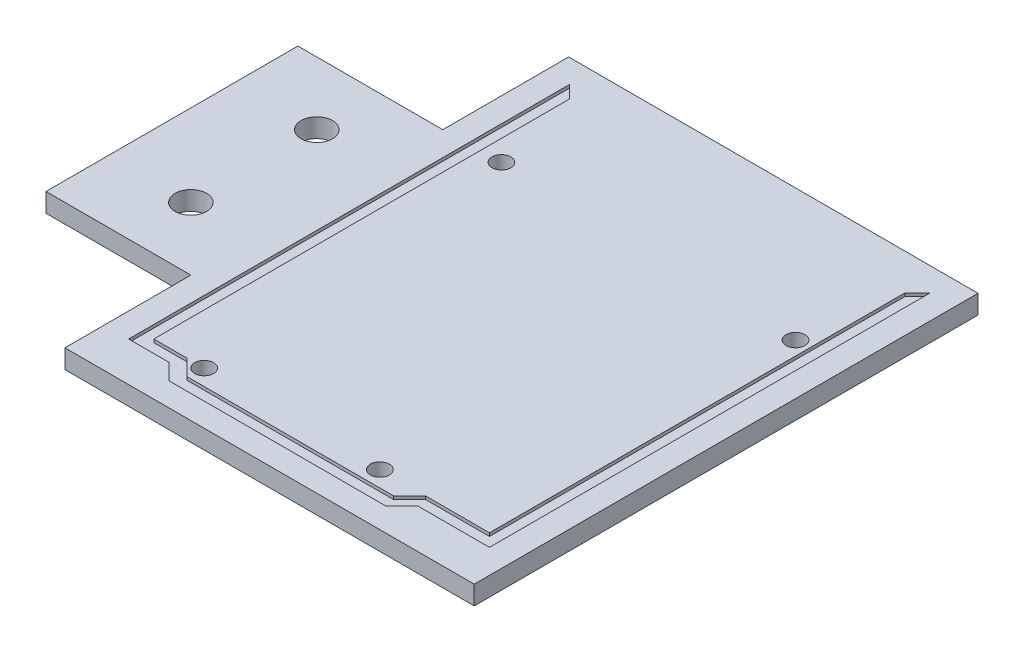
SolidWorks part; units mm, degrees
ref_plane "Front Plane" through (0, 0, 0) normal (0, 0, 1) x (1, 0, 0)
ref_plane "Top Plane" through (0, 0, 0) normal (0, 1, 0) x (1, 0, 0)
ref_plane "Right Plane" through (0, 0, 0) normal (1, 0, 0) x (0, 0, -1)
sketch "Sketch1" plane through (0, 0, 0) normal (0, 0, 1) x (1, 0, 0)
  line L0 (0, 0) -> (0, 23)
  line L1 (0, 23) -> (23, 23)
  line L2 (23, 23) -> (23, 20)
  line L3 (23, 20) -> (3, 20)
  line L4 (3, 20) -> (3, 0)
  line L5 (3, 0) -> (0, 0)
  dimension "D1" = 20
  dimension "D2" = 3
  dimension "D3" = 3
extrude "Boss-Extrude1" add sketch "Sketch1" along normal blind 40
sketch "Sketch2" plane through (0, 23, 0) normal (0, 1, 0) x (1, 0, 0)
  line L0 (23, 0) -> (0, 0) construction
  circle A0 centre (13, -10) radius 2.5
  circle A1 centre (13, -30) radius 2.5
  dimension "D3" = 5
  dimension "D1" = 20
  dimension "D2" = 10
  dimension "D4" = 10
extrude "Cut-Extrude1" cut sketch "Sketch2" against normal up to next
sketch "Sketch3" plane through (0, 0, 0) normal (-1, 0, 0) x (0, 0, 1)
  line L1 (40, 23) -> (40, 0) construction
  line L2 (40, 0) -> (0, 0) construction
  circle A0 centre (10, 10) radius 2.5
  circle A1 centre (30, 10) radius 2.5
  dimension "D1" = 5
  dimension "D2" = 20
  dimension "D3" = 10
  dimension "D4" = 10
extrude "Cut-Extrude2" cut sketch "Sketch3" against normal up to next
fillet "Fillet1" radius 5 2 edges at (1.5, 0, 0) (1.5, 0, 40)
sketch "Sketch4" plane through (0, 23, 0) normal (0, 1, 0) x (1, 0, 0)
  line L0 (-1000, -20) -> (49000, -20) construction
  line L1 (0, -40) -> (0, 0) construction
  line L2 (23, -40) -> (23, 0) construction
  line L3 (88, -60) -> (23, -60)
  line L4 (88, -60) -> (88, 20)
  line L5 (88, 20) -> (23, 20)
  line L6 (23, -60) -> (23, 20)
  line L7 (88, -60) -> (23, 20) construction
  line L8 (88, 20) -> (23, -60) construction
  point P1 (55.5, -20)
  point P5 (0, -20)
  dimension "D1" = 80
  dimension "D2" = 65
extrude "Boss-Extrude2" add sketch "Sketch4" against normal up to surface (3 mm away) up to face at (10.5, 20, 10)
sketch "Sketch5" plane through (0, 23, 0) normal (0, 1, 0) x (1, 0, 0)
  line L0 (28.85, 14.27) -> (28.85, -51.73)
  line L3 (36.65, -54.27) -> (69.45, -54.27)
  line L5 (71.99, -51.73) -> (82.15, -51.73)
  line L6 (82.15, -51.73) -> (82.15, 14.27)
  line L11 (28.85, -51.73) -> (34.11, -51.73)
  line L12 (34.11, -51.73) -> (36.65, -54.27)
  line L14 (69.45, -54.27) -> (71.99, -51.73)
  line L15 (28.85, -51.73) -> (28.85, -54.27) construction
  line L16 (28.85, -54.27) -> (36.65, -54.27) construction
  line L17 (82.15, -51.73) -> (82.15, -54.27) construction
  line L18 (82.15, -54.27) -> (69.45, -54.27) construction
  line L19 (28.85, 14.27) -> (82.15, -54.27) construction
  line L20 (82.15, 14.27) -> (28.85, -54.27) construction
  line L21 (55.5, -980) -> (55.5, 49020) construction
  line L22 (88, 20) -> (23, 20) construction
  line L23 (-1000, -20) -> (49000, -20) construction
  line L24 (0, -40) -> (0, 0) construction
  line L26 (26.85, 16.27) -> (26.85, -53.73)
  line L27 (26.85, -53.73) -> (33.2816, -53.73)
  line L28 (33.2816, -53.73) -> (35.8216, -56.27)
  line L29 (35.8216, -56.27) -> (70.2784, -56.27)
  line L30 (70.2784, -56.27) -> (72.8184, -53.73)
  line L31 (72.8184, -53.73) -> (84.15, -53.73)
  line L32 (84.15, -53.73) -> (84.15, 16.27)
  line L33 (28.85, 14.27) -> (26.85, 16.27)
  line L34 (82.15, 14.27) -> (84.15, 16.27)
  line L35 (82.15, 14.27) -> (28.85, 14.27) construction
  line L36 (84.15, 16.27) -> (26.85, 16.27) construction
  point P15 (55.5, 20)
  point P16 (55.5, -20)
  point P20 (0, -20)
  dimension "D3" = 2.54
  dimension "D7" = 2.54
  dimension "D6" = 2.54
  dimension "D8" = 2.54
  dimension "D1" = 66
  dimension "D2" = 53.3
  dimension "D4" = 12.7
  dimension "D5" = 32.8
  dimension "D9" = 2
extrude "Cut-Extrude3" cut sketch "Sketch5" against normal blind 0.5
sketch "Sketch6" plane through (0, 23, 0) normal (0, 1, 0) x (1, 0, 0)
  line L1 (28.85, -51.73) -> (28.85, 14.27) construction
  circle A0 centre (32.15, 0.17) radius 1.5
  circle A1 centre (79.95, -0.93) radius 1.5
  circle A2 centre (64.75, -51.73) radius 1.5
  circle A3 centre (36.85, -51.73) radius 1.5
  point P8 (65.7968, -51.73)
  point P9 (79.6307, -0.93)
  point P10 (34.35, 3.056)
  point P11 (39.05, -48.4619)
  point P12 (39.05, -48.9274)
  point P14 (78.6714, -0.93)
  dimension "D6" = 3
  dimension "D7" = 15.2
  dimension "D1" = 27.9
  dimension "D2" = 4.7
  dimension "D3" = 50.8
  dimension "D4" = 3.3
  dimension "D5" = 1.1
extrude "Cut-Extrude4" cut sketch "Sketch6" against normal up to next
sketch "Sketch7" plane through (0, 0, 0) normal (-1, 0, 0) x (0, 0, 1)
  line L1 (0, 0) -> (40, 0)
  line L2 (0, 0) -> (0, 20)
  line L3 (0, 20) -> (40, 20)
  line L4 (40, 0) -> (40, 20)
extrude "Cut-Extrude5" cut sketch "Sketch7" against normal up to next
